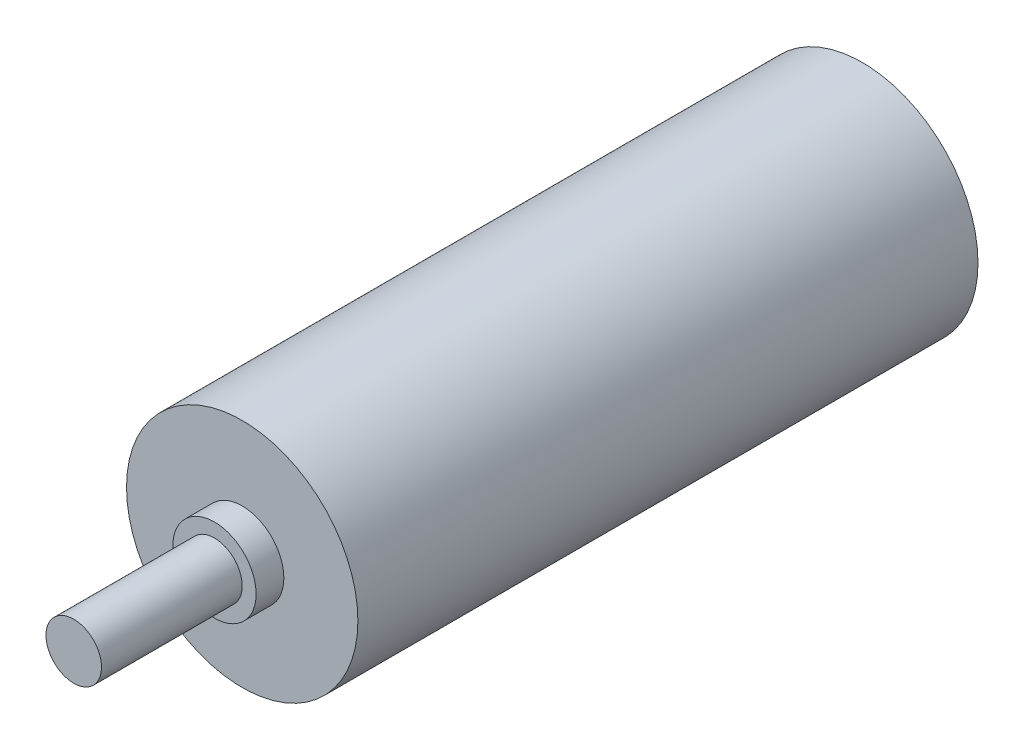
SolidWorks part; units mm, degrees
ref_plane "Plan de face" through (0, 0, 0) normal (0, 0, 1) x (1, 0, 0)
ref_plane "Plan de dessus" through (0, 0, 0) normal (0, 1, 0) x (1, 0, 0)
ref_plane "Plan de droite" through (0, 0, 0) normal (1, 0, 0) x (0, 0, -1)
sketch "Sketch1" plane through (0, 0, 0) normal (0, 0, 1) x (1, 0, 0)
  circle A0 centre (0, 0) radius 12.5
  dimension "D1" = 25
extrude "Boss-Extrude1" add sketch "Sketch1" along normal blind 67
sketch "Sketch2" plane through (0, 0, 67) normal (0, 0, 1) x (1, 0, 0)
  circle A0 centre (0, 0) radius 4.5
  dimension "D1" = 9
extrude "Boss-Extrude3" add sketch "Sketch2" along normal blind 3
sketch "Sketch3" plane through (0, 0, 70) normal (0, 0, 1) x (1, 0, 0)
  circle A0 centre (0, 0) radius 3
  dimension "D1" = 6
extrude "Boss-Extrude4" add sketch "Sketch3" along normal blind 15.2
sketch "Sketch5" plane through (0, 0, 0) normal (0, 0, -1) x (-1, 0, 0)
  circle A0 centre (0, 0) radius 9.5 construction
  dimension "D1" = 19
